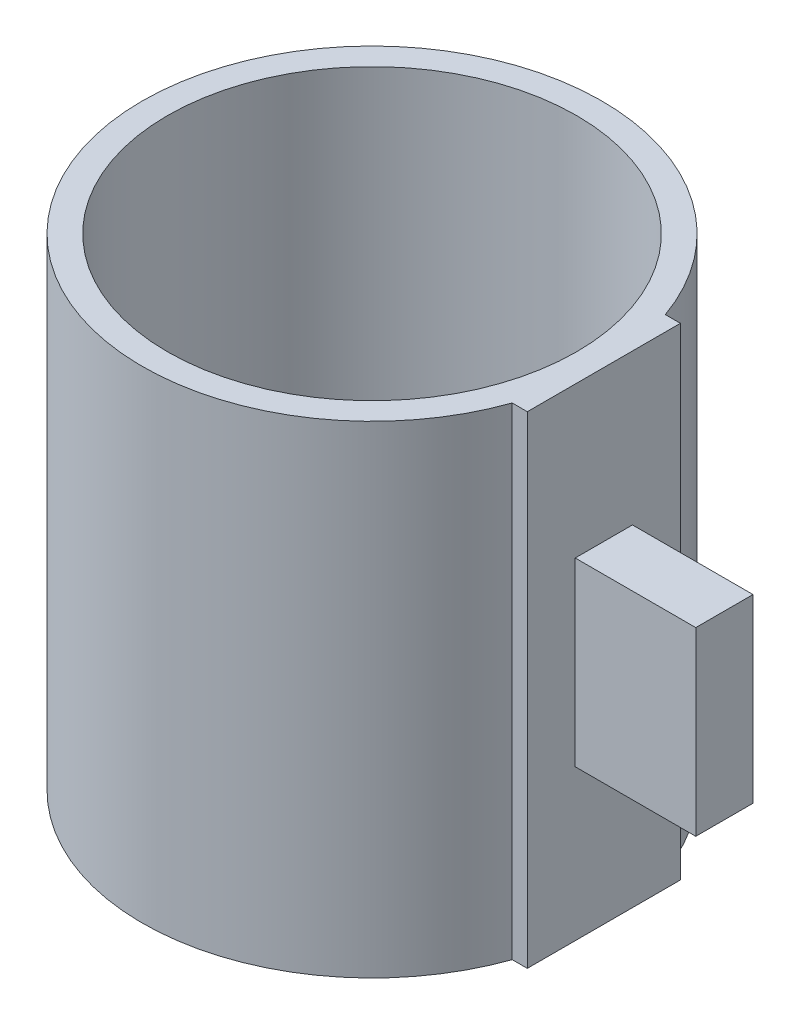
SolidWorks part; units mm, degrees
ref_plane "Front Plane" through (0, 0, 0) normal (0, 0, 1) x (1, 0, 0)
ref_plane "Top Plane" through (0, 0, 0) normal (0, 1, 0) x (1, 0, 0)
ref_plane "Right Plane" through (0, 0, 0) normal (1, 0, 0) x (0, 0, -1)
sketch "Sketch1" plane through (0, 0, 0) normal (0, 1, 0) x (1, 0, 0)
  line L0 (0, -38.14) -> (0, 38.14) construction
  line L1 (0, 0) -> (38.4634, 0) construction
  line L3 (35.9634, -12.7) -> (38.4634, -12.7)
  line L5 (35.9634, 12.7) -> (38.4634, 12.7)
  line L6 (38.4634, -12.7) -> (38.4634, 12.7)
  circle A0 centre (0, 0) radius 33.95
  arc A1 (35.9634, 12.7) -> (35.9634, -12.7) centre (0, 0) ccw
  point P3 (55.9634, 0)
  point P11 (55.9634, -12.7)
  point P12 (0, -38.14)
  dimension "D1" = 67.9
  dimension "D2" = 4.19
  dimension "D4" = 2.5
  dimension "D3" = 25.4
extrude "Boss-Extrude1" add sketch "Sketch1" along normal blind 80
sketch "Sketch2" plane through (38.4634, 0, 0) normal (1, 0, 0) x (0, 0, -1)
  line L0 (0, 80) -> (0, 0) construction
  line L1 (-12.7, 80) -> (12.7, 80) construction
  line L3 (-4.75, 25) -> (4.75, 25)
  line L4 (-4.75, 25) -> (-4.75, 55)
  line L5 (-4.75, 55) -> (4.75, 55)
  line L6 (4.75, 25) -> (4.75, 55)
  line L7 (-4.75, 25) -> (4.75, 55) construction
  line L8 (-4.75, 55) -> (4.75, 25) construction
  point P5 (0, 40)
  dimension "D1" = 9.5
  dimension "D2" = 30
extrude "Boss-Extrude2" add sketch "Sketch2" along normal blind 20
